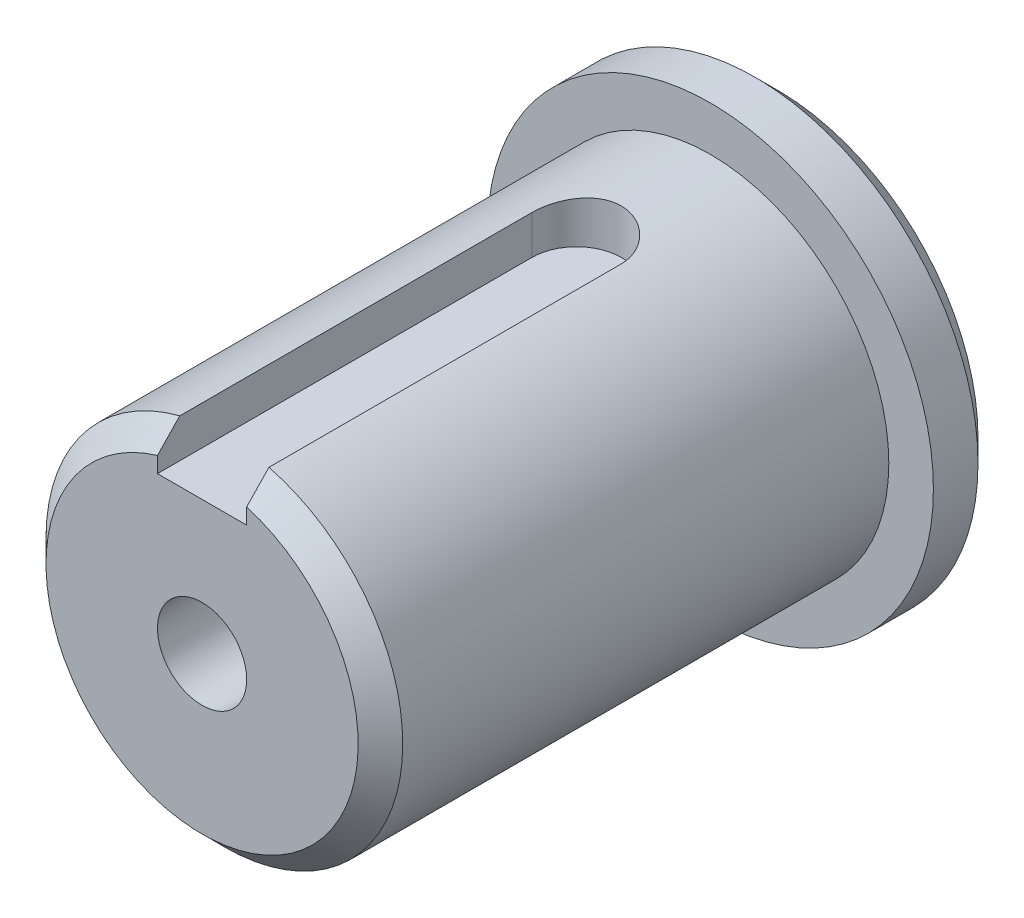
SolidWorks part; units mm, degrees
material "Plain Carbon Steel"
ref_plane "Front" through (0, 0, 0) normal (0, 0, 1) x (1, 0, 0)
ref_plane "Top" through (0, 0, 0) normal (0, 1, 0) x (1, 0, 0)
ref_plane "Right" through (0, 0, 0) normal (1, 0, 0) x (0, 0, -1)
sketch "Sketch1" plane through (0, 0, 0) normal (1, 0, 0) x (0, 0, -1)
  line L0 (0, 2.5) -> (0, 4.5)
  line L1 (0, 4.5) -> (-0.5, 5)
  line L2 (-0.5, 5) -> (-1.5, 5)
  line L3 (-1.5, 5) -> (-1.5, 4)
  line L4 (-1.5, 4) -> (-12.4, 4)
  line L5 (-12.4, 4) -> (-12.9, 3.5)
  line L6 (-12.9, 3.5) -> (-12.9, 1)
  line L7 (-12.9, 1) -> (-8, 1)
  line L8 (-8, 1) -> (-8, 2.5)
  line L9 (-8, 2.5) -> (0, 2.5)
  line L10 (0, 0) -> (3.2083, 0) construction
  point P13 (0, 4)
  point P14 (-10.061, 2.5)
  dimension "D1" = 2
  dimension "D2" = 5
  dimension "D3" = 8
  dimension "D4" = 10
  dimension "D5" = 9
  dimension "D6" = 0.5
  dimension "D7" = 45
  dimension "D8" = 1.5
  dimension "D9" = 45
  dimension "D10" = 11.4
  dimension "D11" = 8
revolve "Revolve1" add sketch "Sketch1" angle 360 about L10
ref_plane "Plane1" through (0, 4, 0) normal (0, 1, 0) x (1, 0, 0)
sketch "Sketch2" plane through (0, 4, 0) normal (0, 1, 0) x (1, 0, 0)
  line L0 (0, -12.9) -> (0, -4.5) construction
  line L1 (-1, -12.9) -> (-1, -4.5)
  line L2 (1, -12.9) -> (1, -4.5)
  line L3 (-3.5, -12.9) -> (3.5, -12.9) construction
  arc A0 (-1, -12.9) -> (1, -12.9) centre (0, -12.9) ccw
  arc A1 (1, -4.5) -> (-1, -4.5) centre (0, -4.5) ccw
  point P3 (0, -8.7)
  point P8 (0, 0)
  dimension "D2" = 9.4
  dimension "D1" = 2
extrude "Cut-Extrude1" cut sketch "Sketch2" against normal blind 1
